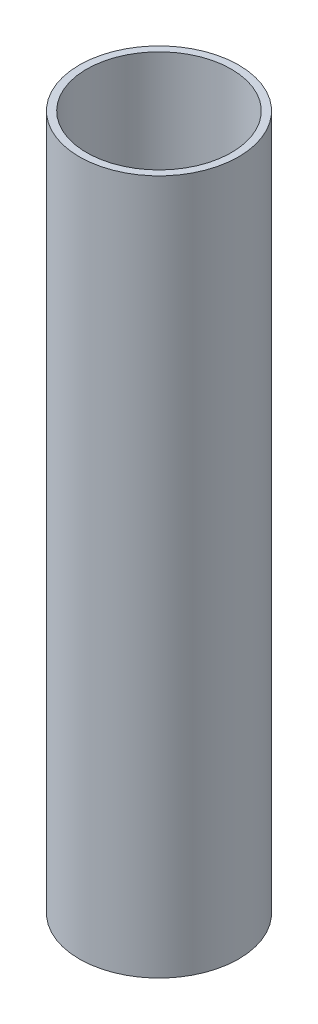
SolidWorks part; units mm, degrees
material "6061 Alloy"
ref_plane "Front Plane" through (0, 0, 0) normal (0, 0, 1) x (1, 0, 0)
ref_plane "Top Plane" through (0, 0, 0) normal (0, 1, 0) x (1, 0, 0)
ref_plane "Right Plane" through (0, 0, 0) normal (1, 0, 0) x (0, 0, -1)
sketch "Sketch1" plane through (0, 0, 0) normal (0, 1, 0) x (1, 0, 0)
  circle A0 centre (0, 0) radius 15.875
  circle A1 centre (0, 0) radius 17.4625
  dimension "D1" = 31.75
  dimension "D2" = 1.5875
extrude "Boss-Extrude1" add sketch "Sketch1" along normal blind 152.4
